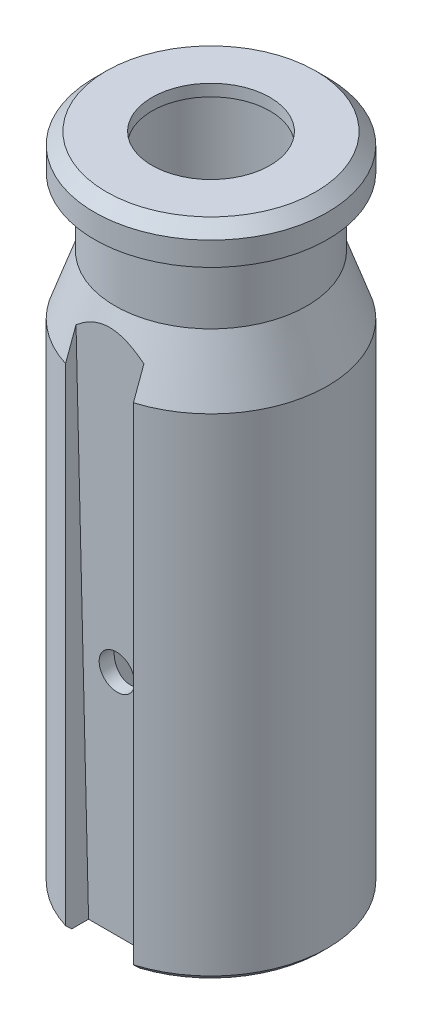
SolidWorks part; units mm, degrees
material "Chrome Stainless Steel"
ref_plane "Front Plane" through (0, 0, 0) normal (0, 0, 1) x (1, 0, 0)
ref_plane "Top Plane" through (0, 0, 0) normal (0, 1, 0) x (1, 0, 0)
ref_plane "Right Plane" through (0, 0, 0) normal (1, 0, 0) x (0, 0, -1)
sketch "MainBodyS" plane through (0, 0, 0) normal (0, 0, 1) x (1, 0, 0)
  line L1 (3.95, 0.2) -> (3.95, 16.7)
  line L2 (3.95, 16.7) -> (3.25, 18.7)
  line L3 (3.25, 18.7) -> (3.25, 21)
  line L4 (3.25, 21) -> (3.95, 21)
  line L5 (3.95, 21) -> (3.95, 21.8)
  line L6 (3.95, 21.8) -> (3.55, 22.2)
  line L7 (3.55, 22.2) -> (2, 22.2)
  line L8 (2, 22.2) -> (2, 21.8)
  line L9 (2, 21.8) -> (2.75, 21.8)
  line L10 (2.75, 21.8) -> (2.75, 4)
  line L11 (1.3, 0) -> (1.3, 4)
  line L12 (1.3, 4) -> (2.75, 4)
  line L13 (0, 0) -> (0, 22.2) construction
  line L14 (1.3, 0) -> (3.75, 0)
  line L15 (3.75, 0) -> (3.95, 0.2)
  dimension "BottomChamferAngle" = 45
  dimension "TopChamferAngle" = 45
  dimension "ChamferHeight" = 0.2
  dimension "TopChamferHeight" = 0.4
  dimension "Height" = 22.2
  dimension "TopHeight" = 1.2
  dimension "HeightMidDia" = 2.3
  dimension "MidDia" = 6.5
  dimension "Dia" = 7.9
  dimension "TopCoverThickness" = 0.4
  dimension "HeightBottomDia" = 4
  dimension "TopHoleDiaControl" = 1.25
  dimension "TopDiaRef" = 4
  dimension "BottomInnerDiaControl" = 2.65
  dimension "RefBottomDia" = 2.6
  dimension "HeightMidChamfer" = 2
  dimension "RefHeightTop" = 5.5
  dimension "RefHeightTopHalf" = 3.5
  dimension "MidInnerDiaControl" = 0.75
  dimension "D20" = 0.5
revolve "MAIN BODY" add sketch "MainBodyS" angle 360 about L13
ref_plane "SLOT END PLANE" through (0, 18.7, 0) normal (0, -1, 0) x (-1, 0, 0)
sketch "LoftedSlotStartS" plane through (0, 0, 0) normal (0, -1, 0) x (-1, 0, 0)
  line L0 (0, 0) -> (0, 3.475) construction
  line L1 (-1.15, 3.95) -> (1.15, 3.95)
  line L2 (-1.15, 3.95) -> (-1.15, 3)
  line L3 (-1.15, 3) -> (1.15, 3)
  line L4 (1.15, 3.95) -> (1.15, 3)
  line L5 (-1.15, 3.95) -> (1.15, 3) construction
  line L6 (-1.15, 3) -> (1.15, 3.95) construction
  circle A0 centre (0, 0) radius 3.95 construction
  point P0 (0, 3.475)
  dimension "Width" = 2.3
  dimension "Height" = 0.95
  dimension "RefHeight" = 3
sketch "LoftedSlotEndS" plane through (0, 18.7, 0) normal (0, -1, 0) x (-1, 0, 0)
  line L1 (-1.15, 3.95) -> (1.15, 3.95)
  line L2 (-1.15, 3.95) -> (-1.15, 3.45)
  line L3 (-1.15, 3.45) -> (1.15, 3.45)
  line L4 (1.15, 3.95) -> (1.15, 3.45)
  line L5 (-1.15, 3.95) -> (1.15, 3.45) construction
  line L6 (-1.15, 3.45) -> (1.15, 3.95) construction
  point P0 (0, 3.7)
  dimension "Height" = 0.5
loft "LOFTED SLOT" cut profiles "LoftedSlotEndS", "LoftedSlotStartS"
mirror "LS HM" about plane through (0, 0, 0) normal (0, 0, 1) of "LOFTED SLOT"
sketch "LocatingHoleS" plane through (0, -0.0722, 2.9983) normal (0, -0.0241, 0.9997) x (1, 0, 0)
  line L0 (0, 0) -> (0, 8) construction
  circle A0 centre (0, 8) radius 0.6
  dimension "Dia" = 1.2
  dimension "Height" = 8
extrude "LOCATING HOLE" cut sketch "LocatingHoleS" against normal up to next
